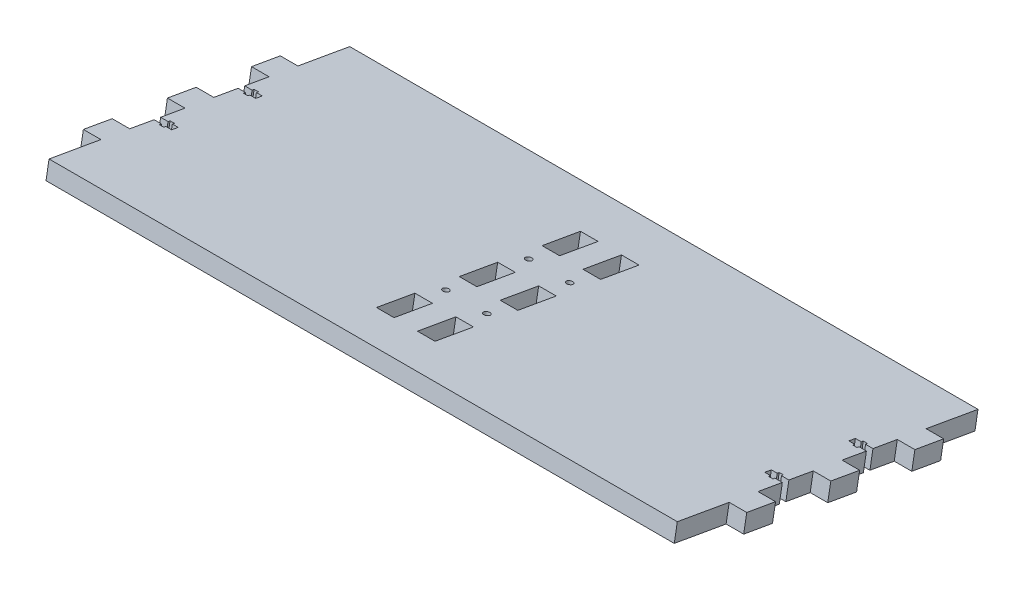
SolidWorks part; units mm, degrees
ref_plane "Front Plane" through (0, 0, 0) normal (0, 0, 1) x (1, 0, 0)
ref_plane "Top Plane" through (0, 0, 0) normal (0, 1, 0) x (1, 0, 0)
ref_plane "Right Plane" through (0, 0, 0) normal (1, 0, 0) x (0, 0, -1)
sketch "Sketch2" plane through (0, -59.9668, 10.5738) normal (0, 0.9848, -0.1736) x (1, 0, 0)
  line L0 (-80, -48.2477) -> (-80, -33.2477) construction
  line L1 (-80, -33.2477) -> (-89, -33.2477) construction
  line L2 (-89, -33.2477) -> (-89, -48.2477) construction
  line L3 (-89, -48.2477) -> (-80, -48.2477) construction
  line L4 (-80, -4.4977) -> (-80, 10.5023) construction
  line L5 (-80, 10.5023) -> (-89, 10.5023) construction
  line L6 (-89, 10.5023) -> (-89, -4.4977) construction
  line L7 (-89, -4.4977) -> (-80, -4.4977) construction
  line L8 (-80, 39.2523) -> (-80, 54.2523) construction
  line L9 (-80, 54.2523) -> (-89, 54.2523) construction
  line L10 (-89, 54.2523) -> (-89, 39.2523) construction
  line L11 (-89, 39.2523) -> (-80, 39.2523) construction
  line L12 (-80, -48.2477) -> (-80, -33.2477) construction
  line L13 (-80, -33.2477) -> (-89, -33.2477)
  line L14 (-89, -33.2477) -> (-89, -48.2477)
  line L15 (-89, -48.2477) -> (-80, -48.2477)
  line L16 (-80, -4.4977) -> (-80, 10.5023) construction
  line L17 (-80, 10.5023) -> (-89, 10.5023)
  line L18 (-89, 10.5023) -> (-89, -4.4977)
  line L19 (-89, -4.4977) -> (-80, -4.4977)
  line L20 (-80, 39.2523) -> (-80, 54.2523) construction
  line L21 (-80, 54.2523) -> (-89, 54.2523)
  line L22 (-89, 54.2523) -> (-89, 39.2523)
  line L23 (-89, 39.2523) -> (-80, 39.2523)
  line L24 (251, 39.2523) -> (251, 54.2523) construction
  line L25 (251, 54.2523) -> (242, 54.2523) construction
  line L26 (242, 54.2523) -> (242, 39.2523) construction
  line L27 (242, 39.2523) -> (251, 39.2523) construction
  line L28 (251, -4.4977) -> (251, 10.5023) construction
  line L29 (251, 10.5023) -> (242, 10.5023) construction
  line L30 (242, 10.5023) -> (242, -4.4977) construction
  line L31 (242, -4.4977) -> (251, -4.4977) construction
  line L32 (251, -48.2477) -> (251, -33.2477) construction
  line L33 (251, -33.2477) -> (242, -33.2477) construction
  line L34 (242, -33.2477) -> (242, -48.2477) construction
  line L35 (242, -48.2477) -> (251, -48.2477) construction
  line L36 (251, 39.2523) -> (251, 54.2523)
  line L37 (251, 54.2523) -> (242, 54.2523)
  line L38 (242, 54.2523) -> (242, 39.2523) construction
  line L39 (242, 39.2523) -> (251, 39.2523)
  line L40 (251, -4.4977) -> (251, 10.5023)
  line L41 (251, 10.5023) -> (242, 10.5023)
  line L42 (242, 10.5023) -> (242, -4.4977) construction
  line L43 (242, -4.4977) -> (251, -4.4977)
  line L44 (251, -48.2477) -> (251, -33.2477)
  line L45 (251, -33.2477) -> (242, -33.2477)
  line L46 (242, -33.2477) -> (242, -48.2477) construction
  line L47 (242, -48.2477) -> (251, -48.2477)
  line L48 (-80, 81.2452) -> (-80, 93.2452) construction
  line L49 (242, 81.2452) -> (-80, 81.2452)
  line L50 (242, 81.2452) -> (242, -75.2407) construction
  line L51 (242, -75.2407) -> (-80, -75.2407)
  line L52 (-80, 81.2452) -> (-80, -75.2407) construction
  line L53 (-80, 81.2452) -> (-80, 93.2452) construction
  line L54 (-80, -87.2407) -> (-80, -75.2407) construction
  line L55 (-80, -87.2407) -> (-80, -75.2407) construction
  line L56 (-80, -75.2407) -> (-80, -48.2477)
  line L57 (-80, -33.2477) -> (-80, -4.4977)
  line L58 (-80, 81.2452) -> (-80, 54.2523)
  line L59 (-80, 39.2523) -> (-80, 10.5023)
  line L60 (242, -48.2477) -> (242, -75.2407)
  line L61 (242, -33.2477) -> (242, -4.4977)
  line L62 (242, 39.2523) -> (242, 10.5023)
  line L63 (242, 81.2452) -> (242, 54.2523)
extrude "Boss-Extrude1" add sketch "Sketch2" along normal blind 9
sketch "Sketch4" plane through (0, -51.1035, 9.0109) normal (0, 0.9848, -0.1736) x (1, 0, 0)
  line L0 (-80, -17.1727) -> (-76.2, -17.1727)
  line L1 (-76.2, -17.1727) -> (-76.2, -16.1227)
  line L2 (-76.2, -16.1227) -> (-74, -16.1227)
  line L3 (-74, -16.1227) -> (-74, -17.1727)
  line L4 (-74, -17.1727) -> (-71, -17.1727)
  line L5 (-71, -17.1727) -> (-71, -20.5727)
  line L6 (-71, -20.5727) -> (-74, -20.5727)
  line L7 (-74, -20.5727) -> (-74, -21.6227)
  line L8 (-74, -21.6227) -> (-76.2, -21.6227)
  line L9 (-76.2, -21.6227) -> (-76.2, -20.5727)
  line L10 (-76.2, -20.5727) -> (-80, -20.5727)
  line L11 (-80, -17.1727) -> (-80, -20.5727)
  line L12 (-80, -18.8727) -> (-71, -18.8727) construction
  line L13 (-80, -4.4977) -> (-80, -33.2477) construction
  line L14 (-89, 10.5023) -> (-89, -4.4977) construction
  line L15 (-89, 3.0023) -> (251, 3.0023) construction
  line L16 (251, -4.4977) -> (251, 10.5023) construction
  line L17 (-80, 24.8773) -> (-71, 24.8773) construction
  line L18 (-80, 23.1773) -> (-80, 26.5773)
  line L19 (-76.2, 26.5773) -> (-80, 26.5773)
  line L20 (-76.2, 27.6273) -> (-76.2, 26.5773)
  line L21 (-74, 27.6273) -> (-76.2, 27.6273)
  line L22 (-74, 26.5773) -> (-74, 27.6273)
  line L23 (-71, 26.5773) -> (-74, 26.5773)
  line L24 (-71, 23.1773) -> (-71, 26.5773)
  line L25 (-74, 23.1773) -> (-71, 23.1773)
  line L26 (-74, 22.1273) -> (-74, 23.1773)
  line L27 (-76.2, 22.1273) -> (-74, 22.1273)
  line L28 (-76.2, 23.1773) -> (-76.2, 22.1273)
  line L29 (-80, 23.1773) -> (-76.2, 23.1773)
  line L30 (81, 81.2452) -> (81, -75.2407) construction
  line L31 (242, 81.2452) -> (-80, 81.2452) construction
  line L32 (-80, -75.2407) -> (242, -75.2407) construction
  line L33 (242, 24.8773) -> (233, 24.8773) construction
  line L34 (242, -18.8727) -> (233, -18.8727) construction
  line L35 (242, 23.1773) -> (238.2, 23.1773)
  line L36 (238.2, 23.1773) -> (238.2, 22.1273)
  line L37 (238.2, 22.1273) -> (236, 22.1273)
  line L38 (236, 22.1273) -> (236, 23.1773)
  line L39 (236, 23.1773) -> (233, 23.1773)
  line L40 (233, 23.1773) -> (233, 26.5773)
  line L41 (233, 26.5773) -> (236, 26.5773)
  line L42 (236, 26.5773) -> (236, 27.6273)
  line L43 (236, 27.6273) -> (238.2, 27.6273)
  line L44 (238.2, 27.6273) -> (238.2, 26.5773)
  line L45 (238.2, 26.5773) -> (242, 26.5773)
  line L46 (242, 23.1773) -> (242, 26.5773)
  line L47 (242, -17.1727) -> (242, -20.5727)
  line L48 (238.2, -20.5727) -> (242, -20.5727)
  line L49 (238.2, -21.6227) -> (238.2, -20.5727)
  line L50 (236, -21.6227) -> (238.2, -21.6227)
  line L51 (236, -20.5727) -> (236, -21.6227)
  line L52 (233, -20.5727) -> (236, -20.5727)
  line L53 (233, -17.1727) -> (233, -20.5727)
  line L54 (236, -17.1727) -> (233, -17.1727)
  line L55 (236, -16.1227) -> (236, -17.1727)
  line L56 (238.2, -16.1227) -> (236, -16.1227)
  line L57 (238.2, -17.1727) -> (238.2, -16.1227)
  line L58 (242, -17.1727) -> (238.2, -17.1727)
  point P16 (-80, -18.8727)
  dimension "D1" = 3.4
  dimension "D2" = 2.2
  dimension "D3" = 18
  dimension "D4" = 3
  dimension "D5" = 5.5
extrude "Cut-Extrude1" cut sketch "Sketch4" against normal through all
sketch "Sketch5" plane through (0, -51.1035, 9.0109) normal (0, 0.9848, -0.1736) x (1, 0, 0)
  line L0 (96, 7.3861) -> (96, -7.3861) construction
  line L1 (96, 50.4714) -> (96, 35.6993) construction
  line L2 (96, -35.6993) -> (96, -50.4714) construction
  line L3 (96, 7.3861) -> (96, -7.3861) construction
  line L4 (96, 50.4714) -> (96, 35.6993) construction
  line L5 (96, -35.6993) -> (96, -50.4714) construction
  line L6 (87, 35.6993) -> (87, 50.4714) construction
  line L7 (87, -7.3861) -> (87, 7.3861) construction
  line L8 (87, -50.4714) -> (87, -35.6993) construction
  line L9 (87, 35.6993) -> (87, 50.4714) construction
  line L10 (87, -7.3861) -> (87, 7.3861) construction
  line L11 (87, -50.4714) -> (87, -35.6993) construction
  line L12 (87, 43.0853) -> (96, 43.0853) construction
  line L13 (87, 0) -> (96, 0) construction
  line L14 (87, -43.0853) -> (96, -43.0853) construction
  line L15 (91.5, 43.0853) -> (91.5, 0) construction
  line L16 (91.5, 0) -> (91.5, -43.0853) construction
  line L18 (87, -53.0853) -> (96, -53.0853)
  line L19 (87, -53.0853) -> (87, -33.0853)
  line L20 (87, -33.0853) -> (96, -33.0853)
  line L21 (96, -53.0853) -> (96, -33.0853)
  line L22 (87, -53.0853) -> (96, -33.0853) construction
  line L23 (87, -33.0853) -> (96, -53.0853) construction
  line L24 (87, 10) -> (96, 10)
  line L25 (87, 10) -> (87, -10)
  line L26 (87, -10) -> (96, -10)
  line L27 (96, 10) -> (96, -10)
  line L28 (87, 10) -> (96, -10) construction
  line L29 (87, -10) -> (96, 10) construction
  line L30 (87, 53.0853) -> (96, 53.0853)
  line L31 (87, 53.0853) -> (87, 33.0853)
  line L32 (87, 33.0853) -> (96, 33.0853)
  line L33 (96, 53.0853) -> (96, 33.0853)
  line L34 (87, 53.0853) -> (96, 33.0853) construction
  line L35 (87, 33.0853) -> (96, 53.0853) construction
  circle A0 centre (91.5, -21.5427) radius 1.6
  circle A1 centre (91.5, 21.5427) radius 1.6
  dimension "D3" = 3.2
  dimension "D1" = 20
  dimension "D2" = 9
extrude "Cut-Extrude2" cut sketch "Sketch5" against normal through all
ref_plane "Plane1" through (81, 0, 0) normal (-1, 0, 0) x (0, 0, 1)
mirror "Mirror1" about plane through (81, 0, 0) normal (-1, 0, 0) of "Cut-Extrude2"
ref_plane "Plane2" through (0, 0, 0) normal (0, 0.1736, 0.9848) x (1, 0, 0)
